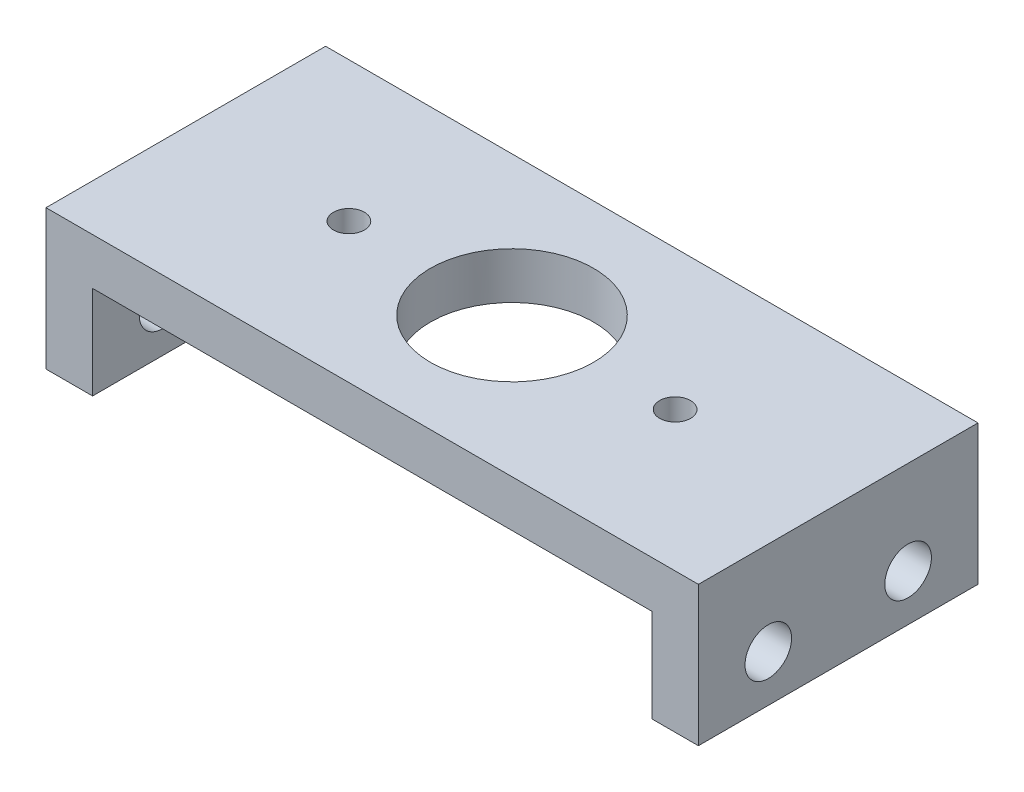
SolidWorks part; units mm, degrees
material "AISI 1015 Steel, Cold Drawn (SS)"
ref_plane "Front Plane" through (0, 0, 0) normal (0, 0, 1) x (1, 0, 0)
ref_plane "Top Plane" through (0, 0, 0) normal (0, 1, 0) x (1, 0, 0)
ref_plane "Right Plane" through (0, 0, 0) normal (1, 0, 0) x (0, 0, -1)
sketch "Sketch1" plane through (0, 0, 0) normal (0, 0, 1) x (1, 0, 0)
  line L0 (0, 0) -> (0, 38.1)
  line L1 (0, 38.1) -> (177.8, 38.1)
  line L2 (177.8, 38.1) -> (177.8, 0)
  line L3 (177.8, 0) -> (165.1, 0)
  line L4 (165.1, 0) -> (165.1, 25.4)
  line L5 (165.1, 25.4) -> (12.7, 25.4)
  line L6 (12.7, 25.4) -> (12.7, 0)
  line L7 (12.7, 0) -> (0, 0)
  dimension "D1" = 177.8
  dimension "D2" = 38.1
  dimension "D3" = 12.7
  dimension "D4" = 12.7
  dimension "D5" = 12.7
extrude "Boss-Extrude1" add sketch "Sketch1" along normal blind 76.2
hole_wizard "3/8 (1.75) Diameter Hole1" positions "Sketch2" profile "Sketch3" hole size "3/8" standard "ANSI Inch" end condition through all
sketch "Sketch2" plane through (0, 38.1, 0) normal (0, 1, 0) x (1, 0, 0)
  line L0 (0, -76.2) -> (0, 0) construction
  line L1 (177.8, -76.2) -> (0, -76.2) construction
  point P0 (88.9, -38.1)
  dimension "D1" = 88.9
  dimension "D2" = 38.1
sketch "Sketch3" plane through (88.9, 38.1, 38.1) normal (1, 0, 0) x (0, 0, 1)
  line L0 (0, 0) -> (0, 38.1)
  line L1 (0, 38.1) -> (22.225, 38.1)
  line L2 (22.225, 38.1) -> (22.225, 0)
  line L5 (22.225, 0) -> (0, 0)
  line L11 (0, -6.35) -> (0, 107.95) construction
  dimension "Thru Hole Dia." = 44.45
  dimension "Thru Hole Depth" = 38.1
hole_wizard "Tap Drill for 3/8-24 Tap1" positions "Sketch4" profile "Sketch5" hole size "3/8-24" standard "ANSI Inch" end condition through all
sketch "Sketch4" plane through (0, 38.1, 0) normal (0, 1, 0) x (1, 0, 0)
  line L0 (177.8, -76.2) -> (0, -76.2) construction
  line L1 (0, -76.2) -> (0, 0) construction
  point P0 (44.45, -38.1)
  point P2 (133.35, -38.1)
  point P7 (0, 0)
  dimension "D1" = 38.1
  dimension "D2" = 44.45
  dimension "D3" = 88.9
sketch "Sketch5" plane through (44.45, 38.1, 38.1) normal (1, 0, 0) x (0, 0, 1)
  line L0 (0, 0) -> (0, 38.1)
  line L1 (0, 38.1) -> (4.2164, 38.1)
  line L2 (4.2164, 38.1) -> (4.2164, 0)
  line L5 (4.2164, 0) -> (0, 0)
  line L11 (0, -6.35) -> (0, 107.95) construction
  dimension "Thru Hole Dia." = 8.4328
  dimension "Thru Hole Depth" = 38.1
hole_wizard "Tap Drill for 3/8-24 Tap2" positions "Sketch6" profile "Sketch7" hole size "3/8-24" standard "ANSI Inch" end condition through all
sketch "Sketch6" plane through (177.8, 0, 0) normal (1, 0, 0) x (0, 0, -1)
  line L0 (-76.2, 0) -> (0, 0) construction
  line L1 (-76.2, 0) -> (-76.2, 38.1) construction
  point P0 (-57.15, 12.7)
  point P2 (-19.05, 12.7)
  point P5 (0, 0)
  dimension "D1" = 12.7
  dimension "D2" = 19.05
  dimension "D3" = 38.1
sketch "Sketch7" plane through (177.8, 12.7, 57.15) normal (0, 1, 0) x (0, 0, -1)
  line L0 (0, 0) -> (0, 177.8)
  line L1 (0, 177.8) -> (6.35, 177.8)
  line L2 (6.35, 177.8) -> (6.35, 0)
  line L5 (6.35, 0) -> (0, 0)
  line L11 (0, -6.35) -> (0, 107.95) construction
  dimension "Thru Hole Dia." = 12.7
  dimension "Thru Hole Depth" = 177.8
